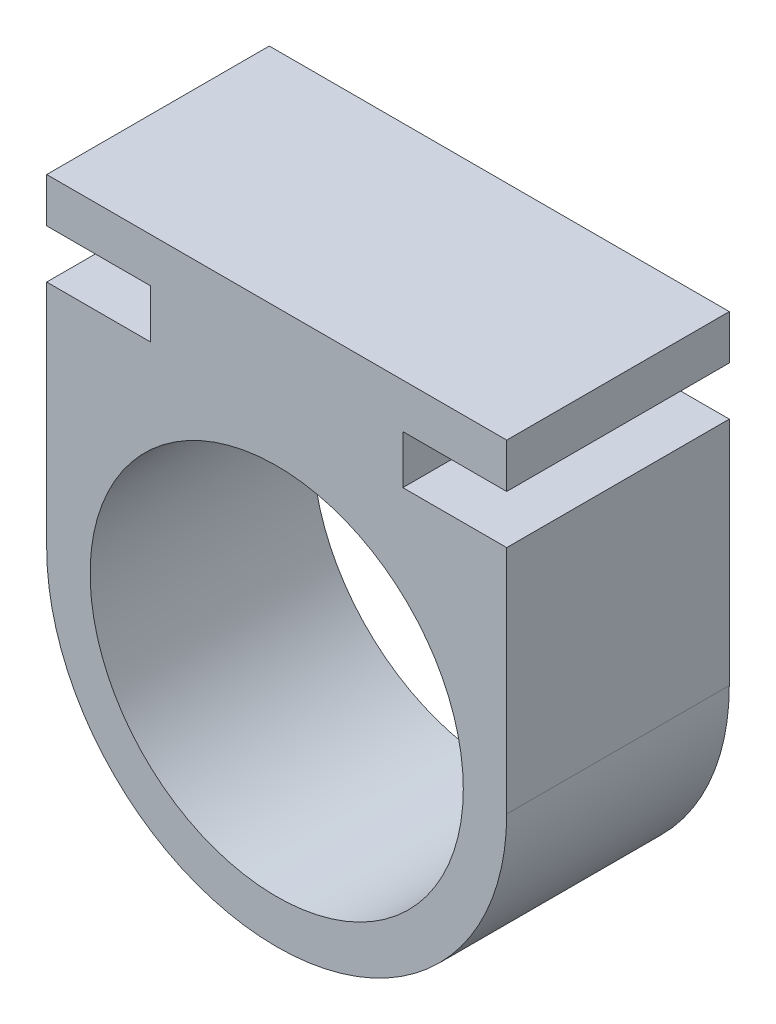
SolidWorks part; units mm, degrees
ref_plane "Front Plane" through (0, 0, 0) normal (0, 0, 1) x (1, 0, 0)
ref_plane "Top Plane" through (0, 0, 0) normal (0, 1, 0) x (1, 0, 0)
ref_plane "Right Plane" through (0, 0, 0) normal (1, 0, 0) x (0, 0, -1)
sketch "Sketch1" plane through (0, 0, 0) normal (0, 0, 1) x (1, 0, 0)
  line L1 (-15.5, 0) -> (15.5, 0)
  line L2 (-15.5, 0) -> (-15.5, 21.825)
  line L3 (-15.5, 21.825) -> (15.5, 21.825)
  line L4 (15.5, 0) -> (15.5, 21.825)
  line L5 (-15.5, 21.825) -> (15.5, 21.825)
  line L6 (-15.5, 21.825) -> (-15.5, 18.825)
  line L7 (-15.5, 18.825) -> (15.5, 18.825)
  line L8 (15.5, 21.825) -> (15.5, 18.825)
  line L9 (15.5, 18.825) -> (-15.5, 18.825)
  line L10 (15.5, 18.825) -> (15.5, 15.55)
  line L11 (15.5, 15.55) -> (-15.5, 15.55)
  line L12 (-15.5, 18.825) -> (-15.5, 15.55)
  line L13 (-15.5, 15.55) -> (-8.5, 15.55)
  line L14 (-15.5, 15.55) -> (-15.5, 21.825)
  line L15 (-15.5, 21.825) -> (-8.5, 21.825)
  line L16 (-8.5, 15.55) -> (-8.5, 21.825)
  line L17 (15.5, 21.825) -> (8.5, 21.825)
  line L18 (15.5, 21.825) -> (15.5, 15.55)
  line L19 (15.5, 15.55) -> (8.5, 15.55)
  line L20 (8.5, 21.825) -> (8.5, 15.55)
  circle A0 centre (0, 0) radius 12.575
  circle A1 centre (0, 0) radius 15.5
  dimension "D1" = 25.15
  dimension "D2" = 31
  dimension "D3" = 31
  dimension "D4" = 21.825
  dimension "D5" = 3
  dimension "D6" = 3.275
  dimension "D7" = 7
  dimension "D8" = 7
extrude "Boss-Extrude1" add sketch "Sketch1" along normal blind 15 contours L3 L20 L7 L4 | L20 L5 L16 L9 | L7 L16 L3 L2 | L20 L9 L16 L11 | A1 L4 L11 L2 | L1 A1 A0 | L1 A1 A0
